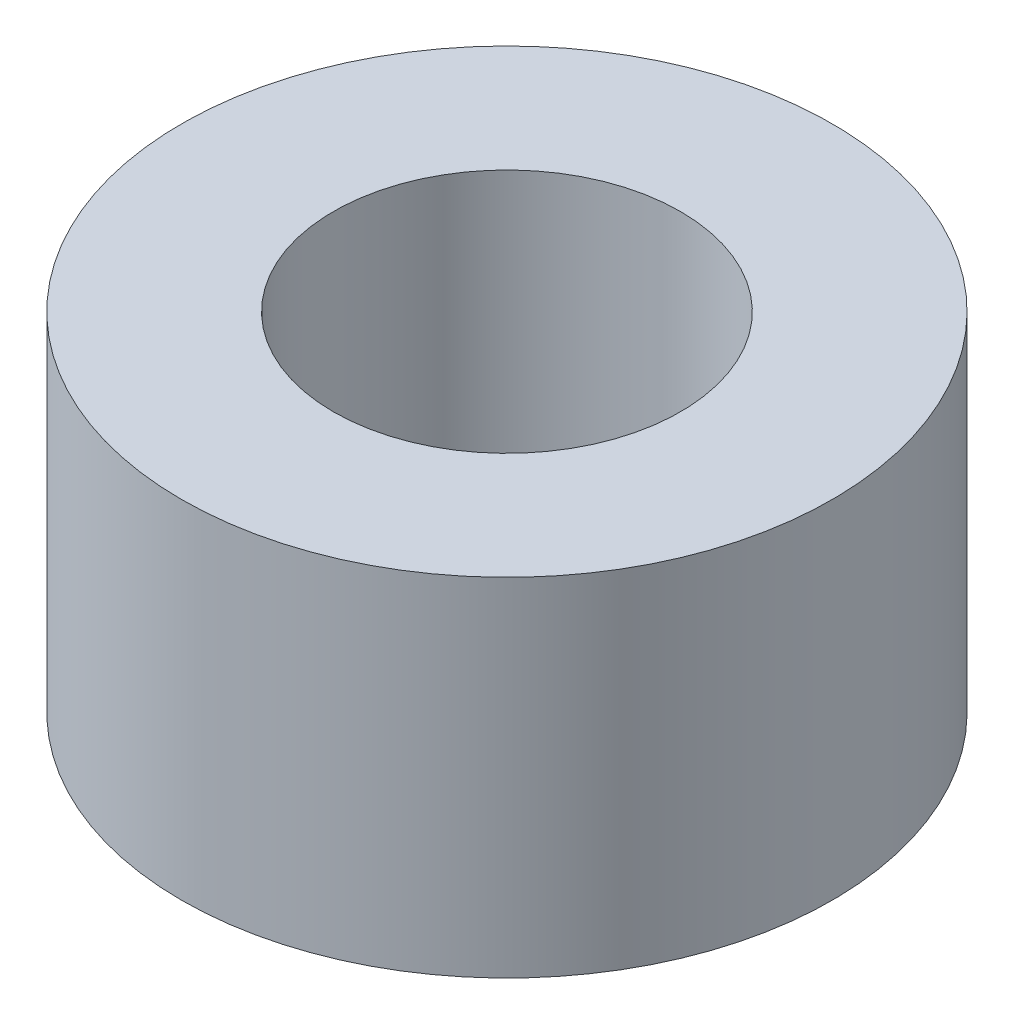
SolidWorks part; units mm, degrees
ref_plane "Front Plane" through (0, 0, 0) normal (0, 0, 1) x (1, 0, 0)
ref_plane "Top Plane" through (0, 0, 0) normal (0, 1, 0) x (1, 0, 0)
ref_plane "Right Plane" through (0, 0, 0) normal (1, 0, 0) x (0, 0, -1)
sketch "Sketch1" plane through (0, 0, 0) normal (0, 1, 0) x (1, 0, 0)
  circle A0 centre (0, 0) radius 11.9062
  circle A1 centre (0, 0) radius 6.35
  dimension "D1" = 12.7
  dimension "D2" = 23.8125
extrude "Boss-Extrude1" add sketch "Sketch1" along normal blind 12.7
